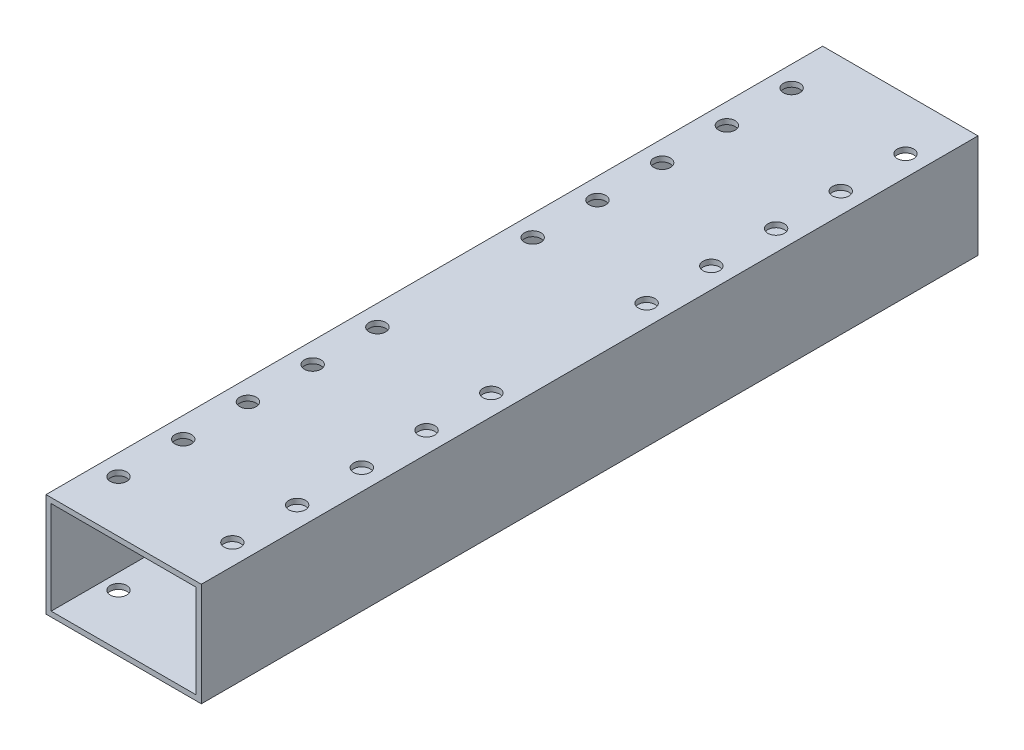
SolidWorks part; units mm, degrees
material "6061-T6 (SS)"
ref_plane "前视基准面" through (0, 0, 0) normal (0, 0, 1) x (1, 0, 0)
ref_plane "上视基准面" through (0, 0, 0) normal (0, 1, 0) x (1, 0, 0)
ref_plane "右视基准面" through (0, 0, 0) normal (1, 0, 0) x (0, 0, -1)
sketch "草图1" plane through (0, 0, 0) normal (0, 0, 1) x (1, 0, 0)
  line L0 (-14, 9) -> (-14, -9)
  line L1 (-15, 10) -> (15, 10)
  line L2 (-15, 10) -> (-15, -10)
  line L3 (-15, -10) -> (15, -10)
  line L4 (15, 10) -> (15, -10)
  line L5 (-15, 10) -> (15, -10) construction
  line L6 (-15, -10) -> (15, 10) construction
  line L7 (-14, -9) -> (14, -9)
  line L8 (14, 9) -> (14, -9)
  line L9 (-14, 9) -> (14, 9)
  point P0 (0, 0)
  dimension "D1" = 30
  dimension "D2" = 20
  dimension "D3" = 1
extrude "凸台-拉伸1" add sketch "草图1" along normal mid plane 150
sketch "草图2" plane through (0, 10, 0) normal (0, 1, 0) x (1, 0, 0)
  line L0 (0, -75) -> (0, 75) construction
  line L1 (15, -75) -> (-15, -75) construction
  line L2 (15, 75) -> (-15, 75) construction
  line L3 (-15, 0) -> (15, 0) construction
  line L4 (-15, -75) -> (-15, 75) construction
  line L5 (15, -75) -> (15, 75) construction
  line L6 (-11, -65) -> (-11, -52.5) construction
  circle A0 centre (-11, -65) radius 1.6
  circle A1 centre (-11, -52.5) radius 1.6
  circle A2 centre (-11, -40) radius 1.6
  circle A3 centre (-11, -27.5) radius 1.6
  circle A4 centre (11, -27.5) radius 1.6
  circle A5 centre (11, -40) radius 1.6
  circle A6 centre (11, -52.5) radius 1.6
  circle A7 centre (11, -65) radius 1.6
  circle A8 centre (11, 27.5) radius 1.6
  circle A9 centre (-11, 27.5) radius 1.6
  circle A10 centre (11, 40) radius 1.6
  circle A11 centre (-11, 40) radius 1.6
  circle A12 centre (11, 52.5) radius 1.6
  circle A13 centre (-11, 52.5) radius 1.6
  circle A14 centre (11, 65) radius 1.6
  circle A15 centre (-11, 65) radius 1.6
  circle A16 centre (-11, -15) radius 1.6
  circle A17 centre (11, -15) radius 1.6
  circle A18 centre (11, 15) radius 1.6
  circle A19 centre (-11, 15) radius 1.6
  dimension "D1" = 10
  dimension "D2" = 3.2
  dimension "D4" = 12.5
  dimension "D5" = 22
  dimension "D3" = 5
extrude "切除-拉伸1" cut sketch "草图2" against normal through all
